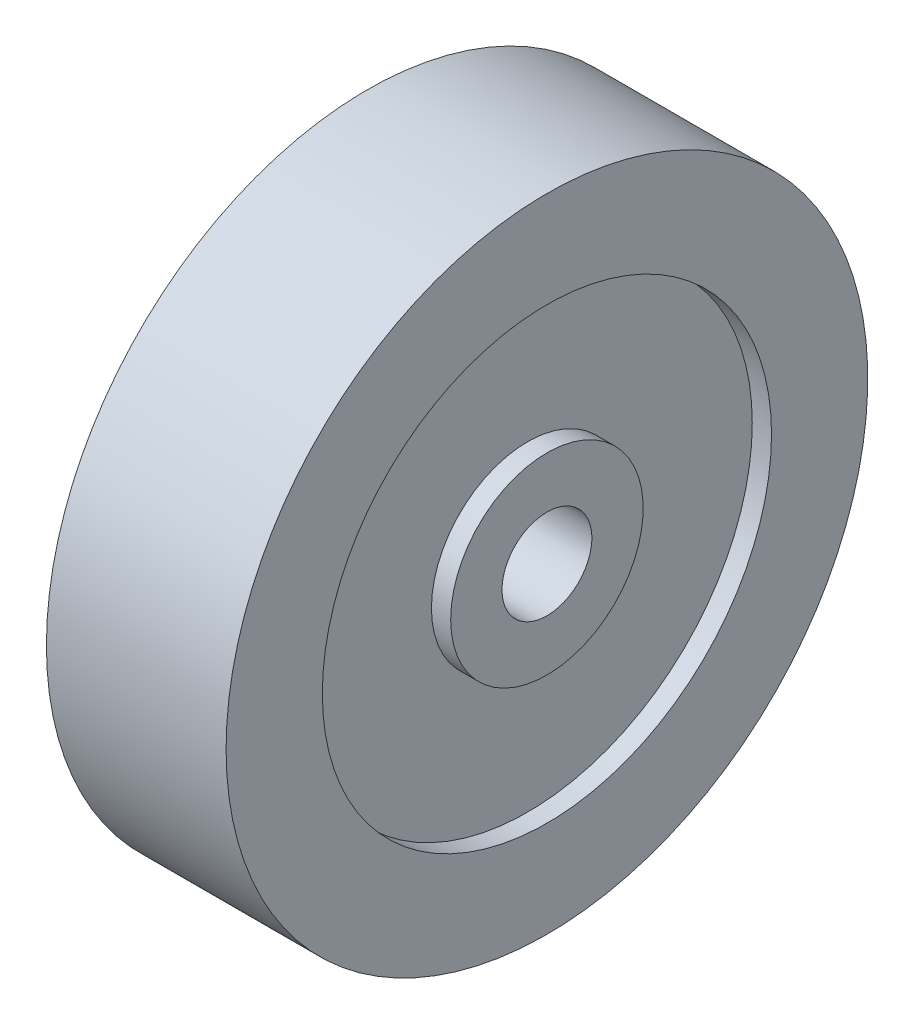
SolidWorks part; units mm, degrees
material "Rubber"
ref_plane "Front Plane" through (0, 0, 0) normal (0, 0, 1) x (1, 0, 0)
ref_plane "Top Plane" through (0, 0, 0) normal (0, 1, 0) x (1, 0, 0)
ref_plane "Right Plane" through (0, 0, 0) normal (1, 0, 0) x (0, 0, -1)
sketch "Sketch1" plane through (0, 0, 0) normal (0, 0, 1) x (1, 0, 0)
  line L0 (0, 0) -> (28, 0)
  line L1 (28, 0) -> (28, 15)
  line L2 (28, 15) -> (25, 15)
  line L3 (25, 15) -> (25, 35)
  line L4 (25, 35) -> (28, 35)
  line L5 (28, 35) -> (28, 43)
  line L6 (28, 43) -> (0, 43)
  line L7 (0, 43) -> (0, 35)
  line L8 (0, 35) -> (3, 35)
  line L9 (3, 35) -> (3, 15)
  line L10 (3, 15) -> (0, 15)
  line L11 (0, 15) -> (0, 0)
  line L12 (-31.9407, 50) -> (59.7333, 50) construction
  point P15 (1.5, 15)
  dimension "D1" = 28
  dimension "D2" = 3
  dimension "D3" = 7
  dimension "D4" = 15
  dimension "D5" = 35
  dimension "D6" = 50
revolve "Revolve1" add sketch "Sketch1" angle 360 about L12
